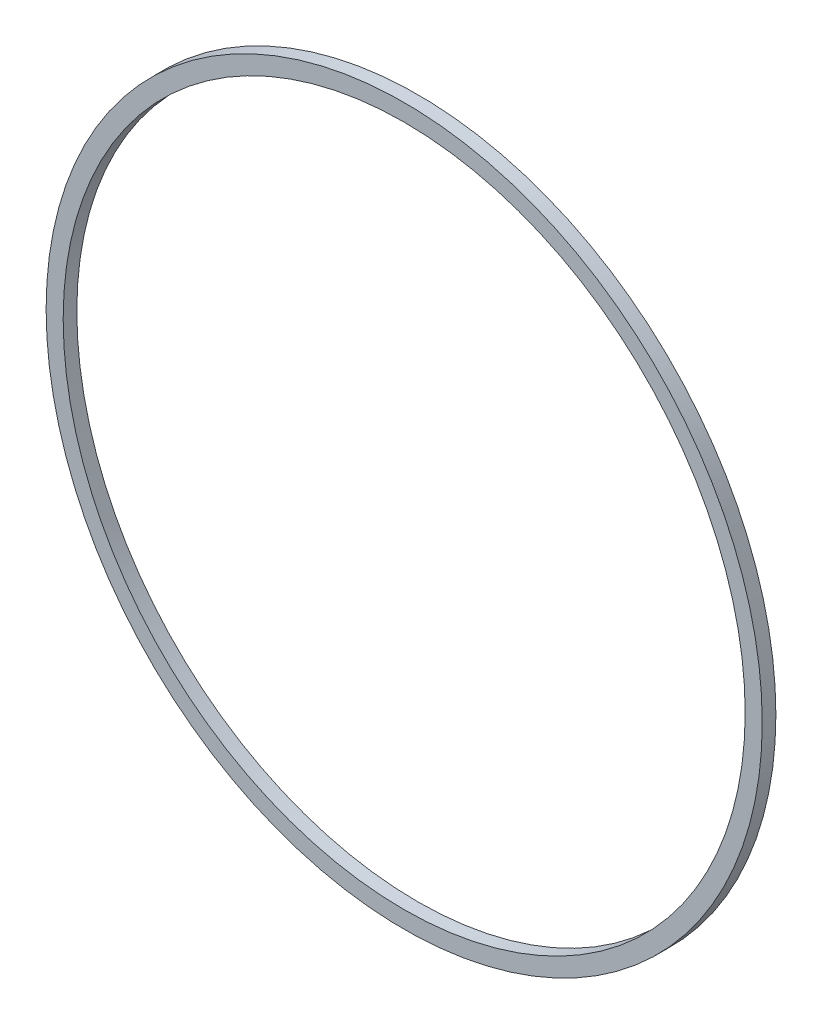
SolidWorks part; units mm, degrees
ref_plane "Front Plane" through (0, 0, 0) normal (0, 0, 1) x (1, 0, 0)
ref_plane "Top Plane" through (0, 0, 0) normal (0, 1, 0) x (1, 0, 0)
ref_plane "Right Plane" through (0, 0, 0) normal (1, 0, 0) x (0, 0, -1)
sketch "Sketch1" plane through (0, 0, 0) normal (0, 0, 1) x (1, 0, 0)
  circle A0 centre (0, 0) radius 50
  circle A1 centre (0, 0) radius 52.5
  dimension "D1" = 105
  dimension "D2" = 100
extrude "Boss-Extrude1" add sketch "Sketch1" along normal blind 2
